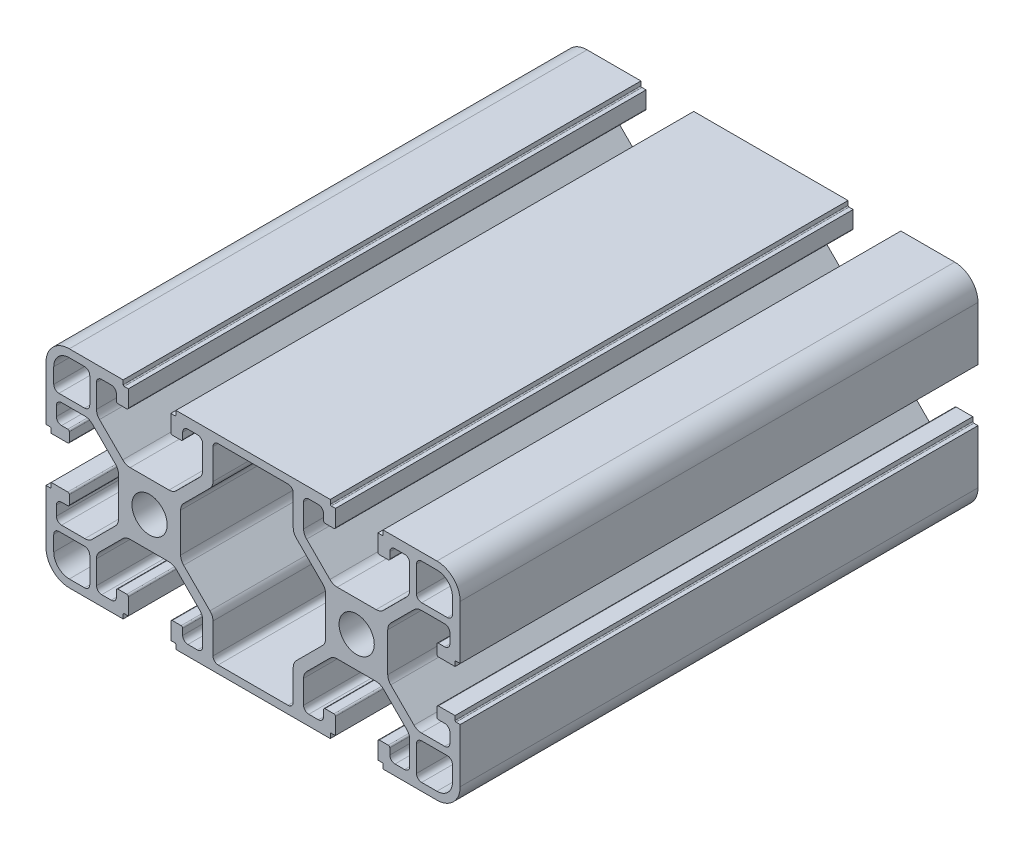
SolidWorks part; units mm, degrees
ref_plane "前视基准面" through (0, 0, 0) normal (0, 0, 1) x (1, 0, 0)
ref_plane "上视基准面" through (0, 0, 0) normal (0, 1, 0) x (1, 0, 0)
ref_plane "右视基准面" through (0, 0, 0) normal (1, 0, 0) x (0, 0, -1)
sketch "草图1" plane through (0, 0, 0) normal (0, 0, 1) x (1, 0, 0)
  line L0 (-24.0688, 18.9402) -> (-34.4688, 18.9402)
  line L1 (-38.9688, 14.4402) -> (-38.9688, 4.0402)
  line L2 (-23.0688, 17.9402) -> (-23.8688, 17.9402)
  line L3 (-24.0688, 18.1402) -> (-24.0688, 18.9402)
  line L4 (-38.9688, 4.0402) -> (-38.1688, 4.0402)
  line L5 (-37.9688, 3.8402) -> (-37.9688, 3.0402)
  line L6 (-31.4614, 9.1902) -> (-35.9688, 9.1902)
  line L7 (-36.9688, 8.1902) -> (-36.9688, 6.3402)
  line L8 (-35.9688, 5.3402) -> (-34.7688, 5.3402)
  line L9 (-34.4688, 5.0402) -> (-34.4688, 3.3402)
  line L10 (-34.7688, 3.0402) -> (-37.9688, 3.0402)
  line L11 (-23.0688, 17.9402) -> (-23.0688, 14.7402)
  line L12 (-23.3688, 14.4402) -> (-25.0688, 14.4402)
  line L13 (-25.3688, 14.7402) -> (-25.3688, 15.9402)
  line L14 (-26.3688, 16.9402) -> (-28.2188, 16.9402)
  line L15 (-29.2188, 15.9402) -> (-29.2188, 11.4328)
  line L16 (-28.633, 10.0186) -> (-24.1404, 5.526)
  line L17 (-22.7261, 4.9402) -> (-15.2114, 4.9402)
  line L18 (-12.9688, 2.6975) -> (-12.9688, -4.8172)
  line L19 (-15.2114, -7.0598) -> (-22.7261, -7.0598)
  line L20 (-24.9688, -4.8172) -> (-24.9688, 2.6975)
  line L21 (-25.5546, 4.1118) -> (-30.0472, 8.6044)
  line L22 (-37.4728, 14.4442) -> (-37.4728, 11.4902)
  line L23 (-36.4728, 10.4902) -> (-31.5188, 10.4902)
  line L24 (-30.5188, 11.4902) -> (-30.5188, 16.4442)
  line L25 (-31.5188, 17.4442) -> (-34.4728, 17.4442)
  line L26 (-13.8688, 18.9402) -> (-3.4688, 18.9402)
  line L27 (-14.8688, 17.9402) -> (-14.0688, 17.9402)
  line L28 (-13.8688, 18.1402) -> (-13.8688, 18.9402)
  line L29 (-14.8688, 17.9402) -> (-14.8688, 14.7402)
  line L30 (-14.5688, 14.4402) -> (-12.8688, 14.4402)
  line L31 (-12.5688, 14.7402) -> (-12.5688, 15.9402)
  line L32 (-11.5688, 16.9402) -> (-9.7188, 16.9402)
  line L33 (-8.7188, 15.9402) -> (-8.7188, 11.4328)
  line L34 (-6.7188, 16.4442) -> (-6.7188, 10.6044)
  line L35 (-9.3046, 10.0186) -> (-13.7972, 5.526)
  line L36 (-12.383, 4.1118) -> (-7.3046, 9.1902)
  line L37 (-5.7188, 17.4442) -> (7.7812, 17.4442)
  line L38 (-24.0688, -21.0598) -> (-34.4688, -21.0598)
  line L39 (-38.9688, -16.5598) -> (-38.9688, -6.1598)
  line L40 (-23.0688, -20.0598) -> (-23.8688, -20.0598)
  line L41 (-24.0688, -20.2598) -> (-24.0688, -21.0598)
  line L42 (-38.9688, -6.1598) -> (-38.1688, -6.1598)
  line L43 (-37.9688, -5.9598) -> (-37.9688, -5.1598)
  line L44 (-31.4614, -11.3098) -> (-35.9688, -11.3098)
  line L45 (-36.9688, -10.3098) -> (-36.9688, -8.4598)
  line L46 (-35.9688, -7.4598) -> (-34.7688, -7.4598)
  line L47 (-34.4688, -7.1598) -> (-34.4688, -5.4598)
  line L48 (-34.7688, -5.1598) -> (-37.9688, -5.1598)
  line L49 (-23.0688, -20.0598) -> (-23.0688, -16.8598)
  line L50 (-23.3688, -16.5598) -> (-25.0688, -16.5598)
  line L51 (-25.3688, -16.8598) -> (-25.3688, -18.0598)
  line L52 (-26.3688, -19.0598) -> (-28.2188, -19.0598)
  line L53 (-29.2188, -18.0598) -> (-29.2188, -13.5525)
  line L54 (-28.633, -12.1382) -> (-24.1404, -7.6456)
  line L55 (-25.5546, -6.2314) -> (-30.0472, -10.724)
  line L56 (-37.4728, -16.5638) -> (-37.4728, -13.6098)
  line L57 (-36.4728, -12.6098) -> (-31.5188, -12.6098)
  line L58 (-30.5188, -13.6098) -> (-30.5188, -18.5638)
  line L59 (-31.5188, -19.5638) -> (-34.4728, -19.5638)
  line L60 (-13.8688, -21.0598) -> (-3.4688, -21.0598)
  line L61 (-14.8688, -20.0598) -> (-14.0688, -20.0598)
  line L62 (-13.8688, -20.2598) -> (-13.8688, -21.0598)
  line L63 (-14.8688, -20.0598) -> (-14.8688, -16.8598)
  line L64 (-14.5688, -16.5598) -> (-12.8688, -16.5598)
  line L65 (-12.5688, -16.8598) -> (-12.5688, -18.0598)
  line L66 (-11.5688, -19.0598) -> (-9.7188, -19.0598)
  line L67 (-8.7188, -18.0598) -> (-8.7188, -13.5525)
  line L68 (-9.3046, -12.1382) -> (-13.7972, -7.6456)
  line L69 (-12.383, -6.2314) -> (-7.3046, -11.3098)
  line L70 (33.5812, -12.6098) -> (38.5352, -12.6098)
  line L71 (39.5352, -13.6098) -> (39.5352, -16.5638)
  line L72 (36.5352, -19.5638) -> (33.5812, -19.5638)
  line L73 (32.5812, -18.5638) -> (32.5812, -13.6098)
  line L74 (32.5812, 11.4902) -> (32.5812, 16.4442)
  line L75 (33.5812, 17.4442) -> (36.5352, 17.4442)
  line L76 (39.5352, 14.4442) -> (39.5352, 11.4902)
  line L77 (38.5352, 10.4902) -> (33.5812, 10.4902)
  line L78 (8.7812, 16.4442) -> (8.7812, 10.6044)
  line L79 (9.367, 9.1902) -> (14.4454, 4.1118)
  line L80 (15.0312, 2.6975) -> (15.0312, -4.8172)
  line L81 (14.4454, -6.2314) -> (9.367, -11.3098)
  line L82 (8.7812, -12.724) -> (8.7812, -18.5638)
  line L83 (5.5312, -21.0598) -> (15.9312, -21.0598)
  line L84 (15.9312, -21.0598) -> (15.9312, -20.2598)
  line L85 (16.1312, -20.0598) -> (16.9312, -20.0598)
  line L86 (16.9312, -20.0598) -> (16.9312, -16.8598)
  line L87 (16.6312, -16.5598) -> (14.9312, -16.5598)
  line L88 (14.6312, -16.8598) -> (14.6312, -18.0598)
  line L89 (13.6312, -19.0598) -> (11.7812, -19.0598)
  line L90 (10.7812, -18.0598) -> (10.7812, -13.5525)
  line L91 (11.367, -12.1382) -> (15.8596, -7.6456)
  line L92 (17.2739, -7.0598) -> (24.7886, -7.0598)
  line L93 (26.2028, -7.6456) -> (30.6954, -12.1382)
  line L94 (31.2812, -13.5525) -> (31.2812, -18.0598)
  line L95 (30.2812, -19.0598) -> (28.4312, -19.0598)
  line L96 (27.4312, -18.0598) -> (27.4312, -16.8598)
  line L97 (27.1312, -16.5598) -> (25.4312, -16.5598)
  line L98 (25.1312, -16.8598) -> (25.1312, -20.0598)
  line L99 (25.1312, -20.0598) -> (25.9312, -20.0598)
  line L100 (26.1312, -20.2598) -> (26.1312, -21.0598)
  line L101 (26.1312, -21.0598) -> (36.5312, -21.0598)
  line L102 (41.0312, -16.5598) -> (41.0312, -6.1598)
  line L103 (41.0312, -6.1598) -> (40.2312, -6.1598)
  line L104 (40.0312, -5.9598) -> (40.0312, -5.1598)
  line L105 (40.0312, -5.1598) -> (36.8312, -5.1598)
  line L106 (36.5312, -5.4598) -> (36.5312, -7.1598)
  line L107 (36.8312, -7.4598) -> (38.0312, -7.4598)
  line L108 (39.0312, -8.4598) -> (39.0312, -10.3098)
  line L109 (38.0312, -11.3098) -> (33.5239, -11.3098)
  line L110 (32.1096, -10.724) -> (27.617, -6.2314)
  line L111 (27.0312, -4.8172) -> (27.0312, 2.6975)
  line L112 (27.617, 4.1118) -> (32.1096, 8.6044)
  line L113 (33.5239, 9.1902) -> (38.0312, 9.1902)
  line L114 (39.0312, 8.1902) -> (39.0312, 6.3402)
  line L115 (38.0312, 5.3402) -> (36.8312, 5.3402)
  line L116 (36.5312, 5.0402) -> (36.5312, 3.3402)
  line L117 (36.8312, 3.0402) -> (40.0312, 3.0402)
  line L118 (40.0312, 3.0402) -> (40.0312, 3.8402)
  line L119 (40.2312, 4.0402) -> (41.0312, 4.0402)
  line L120 (41.0312, 4.0402) -> (41.0312, 14.4402)
  line L121 (36.5312, 18.9402) -> (26.1312, 18.9402)
  line L122 (26.1312, 18.9402) -> (26.1312, 18.1402)
  line L123 (25.9312, 17.9402) -> (25.1312, 17.9402)
  line L124 (25.1312, 17.9402) -> (25.1312, 14.7402)
  line L125 (25.4312, 14.4402) -> (27.1312, 14.4402)
  line L126 (27.4312, 14.7402) -> (27.4312, 15.9402)
  line L127 (28.4312, 16.9402) -> (30.2812, 16.9402)
  line L128 (31.2812, 15.9402) -> (31.2812, 11.4328)
  line L129 (30.6954, 10.0186) -> (26.2028, 5.526)
  line L130 (24.7886, 4.9402) -> (17.2739, 4.9402)
  line L131 (15.8596, 5.526) -> (11.367, 10.0186)
  line L132 (10.7812, 11.4328) -> (10.7812, 15.9402)
  line L133 (11.7812, 16.9402) -> (13.6312, 16.9402)
  line L134 (14.6312, 15.9402) -> (14.6312, 14.7402)
  line L135 (14.9312, 14.4402) -> (16.6312, 14.4402)
  line L136 (16.9312, 14.7402) -> (16.9312, 17.9402)
  line L137 (16.9312, 17.9402) -> (16.1312, 17.9402)
  line L138 (15.9312, 18.1402) -> (15.9312, 18.9402)
  line L139 (15.9312, 18.9402) -> (5.5312, 18.9402)
  line L140 (-3.4688, 18.9402) -> (5.5312, 18.9402)
  line L142 (5.5312, -21.0598) -> (-3.4688, -21.0598)
  line L143 (-6.7188, -18.5638) -> (-6.7188, -12.724)
  line L144 (-5.7188, -19.5638) -> (7.7812, -19.5638)
  arc A0 (-34.4688, 18.9402) -> (-38.9688, 14.4402) centre (-34.4688, 14.4402) ccw
  arc A1 (-24.0688, 18.1402) -> (-23.8688, 17.9402) centre (-23.8688, 18.1402) ccw
  arc A2 (-37.9688, 3.8402) -> (-38.1688, 4.0402) centre (-38.1688, 3.8402) ccw
  arc A3 (-35.9688, 9.1902) -> (-36.9688, 8.1902) centre (-35.9688, 8.1902) ccw
  arc A4 (-36.9688, 6.3402) -> (-35.9688, 5.3402) centre (-35.9688, 6.3402) ccw
  arc A5 (-34.4688, 5.0402) -> (-34.7688, 5.3402) centre (-34.7688, 5.0402) ccw
  arc A6 (-34.7688, 3.0402) -> (-34.4688, 3.3402) centre (-34.7688, 3.3402) ccw
  arc A7 (-23.3688, 14.4402) -> (-23.0688, 14.7402) centre (-23.3688, 14.7402) ccw
  arc A8 (-25.3688, 14.7402) -> (-25.0688, 14.4402) centre (-25.0688, 14.7402) ccw
  arc A9 (-25.3688, 15.9402) -> (-26.3688, 16.9402) centre (-26.3688, 15.9402) ccw
  arc A10 (-28.2188, 16.9402) -> (-29.2188, 15.9402) centre (-28.2188, 15.9402) ccw
  arc A11 (-29.2188, 11.4328) -> (-28.633, 10.0186) centre (-27.2188, 11.4328) ccw
  arc A12 (-24.1404, 5.526) -> (-22.7261, 4.9402) centre (-22.7261, 6.9402) ccw
  arc A13 (-24.9688, 2.6975) -> (-25.5546, 4.1118) centre (-26.9688, 2.6975) ccw
  circle A14 centre (-18.9688, -1.0598) radius 3.4
  arc A15 (-30.0472, 8.6044) -> (-31.4614, 9.1902) centre (-31.4614, 7.1902) ccw
  arc A16 (-37.4728, 11.4902) -> (-36.4728, 10.4902) centre (-36.4728, 11.4902) ccw
  arc A17 (-31.5188, 10.4902) -> (-30.5188, 11.4902) centre (-31.5188, 11.4902) ccw
  arc A18 (-30.5188, 16.4442) -> (-31.5188, 17.4442) centre (-31.5188, 16.4442) ccw
  arc A19 (-34.4728, 17.4442) -> (-37.4728, 14.4442) centre (-34.4728, 14.4442) ccw
  arc A20 (-14.0688, 17.9402) -> (-13.8688, 18.1402) centre (-14.0688, 18.1402) ccw
  arc A21 (-14.8688, 14.7402) -> (-14.5688, 14.4402) centre (-14.5688, 14.7402) ccw
  arc A22 (-12.8688, 14.4402) -> (-12.5688, 14.7402) centre (-12.8688, 14.7402) ccw
  arc A23 (-11.5688, 16.9402) -> (-12.5688, 15.9402) centre (-11.5688, 15.9402) ccw
  arc A24 (-8.7188, 15.9402) -> (-9.7188, 16.9402) centre (-9.7188, 15.9402) ccw
  arc A25 (-7.3046, 9.1902) -> (-6.7188, 10.6044) centre (-8.7188, 10.6044) ccw
  arc A26 (-9.3046, 10.0186) -> (-8.7188, 11.4328) centre (-10.7188, 11.4328) ccw
  arc A27 (-15.2114, 4.9402) -> (-13.7972, 5.526) centre (-15.2114, 6.9402) ccw
  arc A28 (-12.383, 4.1118) -> (-12.9688, 2.6975) centre (-10.9688, 2.6975) ccw
  arc A29 (-5.7188, 17.4442) -> (-6.7188, 16.4442) centre (-5.7188, 16.4442) ccw
  arc A30 (-38.9688, -16.5598) -> (-34.4688, -21.0598) centre (-34.4688, -16.5598) ccw
  arc A31 (-23.8688, -20.0598) -> (-24.0688, -20.2598) centre (-23.8688, -20.2598) ccw
  arc A32 (-38.1688, -6.1598) -> (-37.9688, -5.9598) centre (-38.1688, -5.9598) ccw
  arc A33 (-36.9688, -10.3098) -> (-35.9688, -11.3098) centre (-35.9688, -10.3098) ccw
  arc A34 (-35.9688, -7.4598) -> (-36.9688, -8.4598) centre (-35.9688, -8.4598) ccw
  arc A35 (-34.7688, -7.4598) -> (-34.4688, -7.1598) centre (-34.7688, -7.1598) ccw
  arc A36 (-34.4688, -5.4598) -> (-34.7688, -5.1598) centre (-34.7688, -5.4598) ccw
  arc A37 (-23.0688, -16.8598) -> (-23.3688, -16.5598) centre (-23.3688, -16.8598) ccw
  arc A38 (-25.0688, -16.5598) -> (-25.3688, -16.8598) centre (-25.0688, -16.8598) ccw
  arc A39 (-26.3688, -19.0598) -> (-25.3688, -18.0598) centre (-26.3688, -18.0598) ccw
  arc A40 (-29.2188, -18.0598) -> (-28.2188, -19.0598) centre (-28.2188, -18.0598) ccw
  arc A41 (-28.633, -12.1382) -> (-29.2188, -13.5525) centre (-27.2188, -13.5525) ccw
  arc A42 (-22.7261, -7.0598) -> (-24.1404, -7.6456) centre (-22.7261, -9.0598) ccw
  arc A43 (-25.5546, -6.2314) -> (-24.9688, -4.8172) centre (-26.9688, -4.8172) ccw
  arc A44 (-31.4614, -11.3098) -> (-30.0472, -10.724) centre (-31.4614, -9.3098) ccw
  arc A45 (-36.4728, -12.6098) -> (-37.4728, -13.6098) centre (-36.4728, -13.6098) ccw
  arc A46 (-30.5188, -13.6098) -> (-31.5188, -12.6098) centre (-31.5188, -13.6098) ccw
  arc A47 (-31.5188, -19.5638) -> (-30.5188, -18.5638) centre (-31.5188, -18.5638) ccw
  arc A48 (-37.4728, -16.5638) -> (-34.4728, -19.5638) centre (-34.4728, -16.5638) ccw
  arc A49 (-13.8688, -20.2598) -> (-14.0688, -20.0598) centre (-14.0688, -20.2598) ccw
  arc A50 (-14.5688, -16.5598) -> (-14.8688, -16.8598) centre (-14.5688, -16.8598) ccw
  arc A51 (-12.5688, -16.8598) -> (-12.8688, -16.5598) centre (-12.8688, -16.8598) ccw
  arc A52 (-12.5688, -18.0598) -> (-11.5688, -19.0598) centre (-11.5688, -18.0598) ccw
  arc A53 (-9.7188, -19.0598) -> (-8.7188, -18.0598) centre (-9.7188, -18.0598) ccw
  arc A54 (-8.7188, -13.5525) -> (-9.3046, -12.1382) centre (-10.7188, -13.5525) ccw
  arc A55 (-13.7972, -7.6456) -> (-15.2114, -7.0598) centre (-15.2114, -9.0598) ccw
  arc A56 (-12.9688, -4.8172) -> (-12.383, -6.2314) centre (-10.9688, -4.8172) ccw
  arc A57 (39.5352, -13.6098) -> (38.5352, -12.6098) centre (38.5352, -13.6098) ccw
  arc A58 (36.5352, -19.5638) -> (39.5352, -16.5638) centre (36.5352, -16.5638) ccw
  arc A59 (32.5812, -18.5638) -> (33.5812, -19.5638) centre (33.5812, -18.5638) ccw
  arc A60 (33.5812, -12.6098) -> (32.5812, -13.6098) centre (33.5812, -13.6098) ccw
  arc A61 (33.5812, 17.4442) -> (32.5812, 16.4442) centre (33.5812, 16.4442) ccw
  arc A62 (39.5352, 14.4442) -> (36.5352, 17.4442) centre (36.5352, 14.4442) ccw
  arc A63 (38.5352, 10.4902) -> (39.5352, 11.4902) centre (38.5352, 11.4902) ccw
  arc A64 (32.5812, 11.4902) -> (33.5812, 10.4902) centre (33.5812, 11.4902) ccw
  circle A65 centre (21.0312, -1.0598) radius 3.4
  arc A66 (8.7812, 10.6044) -> (9.367, 9.1902) centre (10.7812, 10.6044) ccw
  arc A67 (15.0312, 2.6975) -> (14.4454, 4.1118) centre (13.0312, 2.6975) ccw
  arc A68 (14.4454, -6.2314) -> (15.0312, -4.8172) centre (13.0312, -4.8172) ccw
  arc A69 (9.367, -11.3098) -> (8.7812, -12.724) centre (10.7812, -12.724) ccw
  arc A70 (16.1312, -20.0598) -> (15.9312, -20.2598) centre (16.1312, -20.2598) ccw
  arc A71 (16.9312, -16.8598) -> (16.6312, -16.5598) centre (16.6312, -16.8598) ccw
  arc A72 (14.9312, -16.5598) -> (14.6312, -16.8598) centre (14.9312, -16.8598) ccw
  arc A73 (13.6312, -19.0598) -> (14.6312, -18.0598) centre (13.6312, -18.0598) ccw
  arc A74 (10.7812, -18.0598) -> (11.7812, -19.0598) centre (11.7812, -18.0598) ccw
  arc A75 (11.367, -12.1382) -> (10.7812, -13.5525) centre (12.7812, -13.5525) ccw
  arc A76 (17.2739, -7.0598) -> (15.8596, -7.6456) centre (17.2739, -9.0598) ccw
  arc A77 (26.2028, -7.6456) -> (24.7886, -7.0598) centre (24.7886, -9.0598) ccw
  arc A78 (31.2812, -13.5525) -> (30.6954, -12.1382) centre (29.2812, -13.5525) ccw
  arc A79 (30.2812, -19.0598) -> (31.2812, -18.0598) centre (30.2812, -18.0598) ccw
  arc A80 (27.4312, -18.0598) -> (28.4312, -19.0598) centre (28.4312, -18.0598) ccw
  arc A81 (27.4312, -16.8598) -> (27.1312, -16.5598) centre (27.1312, -16.8598) ccw
  arc A82 (25.4312, -16.5598) -> (25.1312, -16.8598) centre (25.4312, -16.8598) ccw
  arc A83 (26.1312, -20.2598) -> (25.9312, -20.0598) centre (25.9312, -20.2598) ccw
  arc A84 (36.5312, -21.0598) -> (41.0312, -16.5598) centre (36.5312, -16.5598) ccw
  arc A85 (40.0312, -5.9598) -> (40.2312, -6.1598) centre (40.2312, -5.9598) ccw
  arc A86 (36.8312, -5.1598) -> (36.5312, -5.4598) centre (36.8312, -5.4598) ccw
  arc A87 (36.5312, -7.1598) -> (36.8312, -7.4598) centre (36.8312, -7.1598) ccw
  arc A88 (39.0312, -8.4598) -> (38.0312, -7.4598) centre (38.0312, -8.4598) ccw
  arc A89 (38.0312, -11.3098) -> (39.0312, -10.3098) centre (38.0312, -10.3098) ccw
  arc A90 (32.1096, -10.724) -> (33.5239, -11.3098) centre (33.5239, -9.3098) ccw
  arc A91 (27.0312, -4.8172) -> (27.617, -6.2314) centre (29.0312, -4.8172) ccw
  arc A92 (27.617, 4.1118) -> (27.0312, 2.6975) centre (29.0312, 2.6975) ccw
  arc A93 (33.5239, 9.1902) -> (32.1096, 8.6044) centre (33.5239, 7.1902) ccw
  arc A94 (39.0312, 8.1902) -> (38.0312, 9.1902) centre (38.0312, 8.1902) ccw
  arc A95 (38.0312, 5.3402) -> (39.0312, 6.3402) centre (38.0312, 6.3402) ccw
  arc A96 (36.8312, 5.3402) -> (36.5312, 5.0402) centre (36.8312, 5.0402) ccw
  arc A97 (36.5312, 3.3402) -> (36.8312, 3.0402) centre (36.8312, 3.3402) ccw
  arc A98 (40.2312, 4.0402) -> (40.0312, 3.8402) centre (40.2312, 3.8402) ccw
  arc A99 (41.0312, 14.4402) -> (36.5312, 18.9402) centre (36.5312, 14.4402) ccw
  arc A100 (25.9312, 17.9402) -> (26.1312, 18.1402) centre (25.9312, 18.1402) ccw
  arc A101 (25.1312, 14.7402) -> (25.4312, 14.4402) centre (25.4312, 14.7402) ccw
  arc A102 (27.1312, 14.4402) -> (27.4312, 14.7402) centre (27.1312, 14.7402) ccw
  arc A103 (28.4312, 16.9402) -> (27.4312, 15.9402) centre (28.4312, 15.9402) ccw
  arc A104 (31.2812, 15.9402) -> (30.2812, 16.9402) centre (30.2812, 15.9402) ccw
  arc A105 (30.6954, 10.0186) -> (31.2812, 11.4328) centre (29.2812, 11.4328) ccw
  arc A106 (24.7886, 4.9402) -> (26.2028, 5.526) centre (24.7886, 6.9402) ccw
  arc A107 (15.8596, 5.526) -> (17.2739, 4.9402) centre (17.2739, 6.9402) ccw
  arc A108 (10.7812, 11.4328) -> (11.367, 10.0186) centre (12.7812, 11.4328) ccw
  arc A109 (11.7812, 16.9402) -> (10.7812, 15.9402) centre (11.7812, 15.9402) ccw
  arc A110 (14.6312, 15.9402) -> (13.6312, 16.9402) centre (13.6312, 15.9402) ccw
  arc A111 (14.6312, 14.7402) -> (14.9312, 14.4402) centre (14.9312, 14.7402) ccw
  arc A112 (16.6312, 14.4402) -> (16.9312, 14.7402) centre (16.6312, 14.7402) ccw
  arc A113 (15.9312, 18.1402) -> (16.1312, 17.9402) centre (16.1312, 18.1402) ccw
  arc A114 (8.7812, 16.4442) -> (7.7812, 17.4442) centre (7.7812, 16.4442) ccw
  arc A115 (-6.7188, -12.724) -> (-7.3046, -11.3098) centre (-8.7188, -12.724) ccw
  arc A116 (-6.7188, -18.5638) -> (-5.7188, -19.5638) centre (-5.7188, -18.5638) ccw
  arc A117 (7.7812, -19.5638) -> (8.7812, -18.5638) centre (7.7812, -18.5638) ccw
extrude "凸台-拉伸1" add sketch "草图1" along normal blind 100
